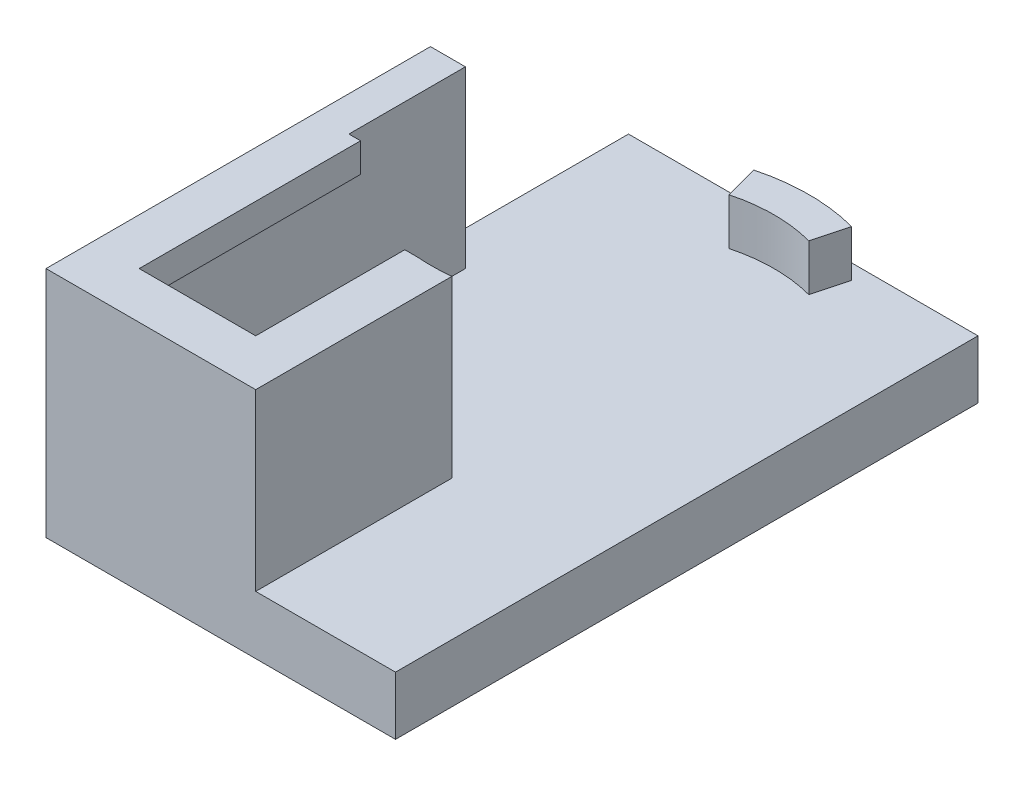
SolidWorks part; units mm, degrees
ref_plane "Front Plane" through (0, 0, 0) normal (0, 0, 1) x (1, 0, 0)
ref_plane "Top Plane" through (0, 0, 0) normal (0, 1, 0) x (1, 0, 0)
ref_plane "Right Plane" through (0, 0, 0) normal (1, 0, 0) x (0, 0, -1)
sketch "Sketch1" plane through (0, 0, 0) normal (0, 1, 0) x (1, 0, 0)
  line L1 (-22.5, 42.5) -> (22.5, 42.5)
  line L2 (-22.5, 42.5) -> (-22.5, -42.5)
  line L3 (-22.5, -42.5) -> (22.5, -42.5)
  line L4 (22.5, 42.5) -> (22.5, -42.5)
  line L5 (-22.5, 42.5) -> (22.5, -42.5) construction
  line L6 (-22.5, -42.5) -> (22.5, 42.5) construction
  point P0 (0, 0)
  dimension "D1" = 45
  dimension "D2" = 85
extrude "Boss-Extrude1" add sketch "Sketch1" along normal blind 100
shell "Shell1" thickness 5
sketch "Sketch2" plane through (0, 5, 0) normal (0, 1, 0) x (1, 0, 0)
  line L0 (-13.25, 0) -> (-13.25, -30)
  line L1 (-13.25, -30) -> (-1.25, -30)
  line L2 (-1.25, -30) -> (-1.25, -13.0576)
  line L3 (-16.25, 0) -> (-16.25, -33)
  line L4 (-16.25, -33) -> (1.75, -33)
  line L5 (1.75, -33) -> (1.75, -13.0576)
  line L6 (-13.25, 0) -> (-16.25, 0)
  line L7 (3.4294, 12.7985) -> (4.2058, 15.6963)
  line L8 (-4.2058, 15.6963) -> (-3.4294, 12.7985)
  line L19 (-1.25, -13.0576) -> (-1.25, -16.2019)
  line L20 (-13.25, -25) -> (-16.25, -25)
  line L21 (-16.25, -15) -> (-13.25, -15)
  circle A1 centre (0, 0) radius 16.25
  circle A2 centre (0, 0) radius 13.25
  dimension "D1" = 26.5
  dimension "D2" = 32.5
  dimension "D3" = 12
  dimension "D4" = 30
  dimension "D6" = 15
  dimension "D8" = 10
  dimension "D9" = 8
  dimension "D5" = 3
extrude "Boss-Extrude2" add sketch "Sketch2" along normal blind 15 contours A1 L2 L1 L0 L20 L3 L4 L5 | L21 L3 L20 L0 | A1 L3 L21 L0 | A2 L7 A1 L8 | L6 A1 L0
sketch "Sketch4" plane through (-13.25, 0, 0) normal (1, 0, 0) x (0, 0, -1)
  line L0 (0, 5) -> (-30, 5) construction
  line L1 (-30, 20) -> (-10, 20)
  line L2 (-30, 20) -> (-30, 17.5)
  line L3 (-30, 17.5) -> (-10, 17.5)
  line L4 (-10, 20) -> (-10, 17.5)
  dimension "D1" = 12.5
  dimension "D2" = 20
extrude "Boss-Extrude3" add sketch "Sketch4" along normal blind 1
sketch "Sketch5" plane through (-1.25, 0, 0) normal (-1, 0, 0) x (0, 0, 1)
  line L0 (30, 20) -> (30, 5) construction
  line L1 (16.2019, 20) -> (30, 20)
  line L2 (16.2019, 20) -> (16.2019, 17.5)
  line L3 (16.2019, 17.5) -> (30, 17.5)
  line L4 (30, 20) -> (30, 17.5)
  line L5 (30, 5) -> (16.2019, 5) construction
  dimension "D1" = 12.5
extrude "Boss-Extrude4" add sketch "Sketch5" along normal blind 1
sketch "Sketch6" plane through (0, 0, 30) normal (0, 0, -1) x (-1, 0, 0)
  line L2 (12.25, 17.5) -> (2.25, 17.5)
  line L3 (12.25, 17.5) -> (12.25, 20)
  line L4 (12.25, 20) -> (2.25, 20)
  line L5 (2.25, 17.5) -> (2.25, 20)
extrude "Boss-Extrude5" add sketch "Sketch6" along normal blind 1
sketch "Sketch9" plane through (0, 20, 0) normal (0, 1, 0) x (1, 0, 0)
  line L1 (-5.0753, 17.3777) -> (5.4023, 17.3777)
  line L2 (-5.0753, 17.3777) -> (-5.0753, 11.055)
  line L3 (-5.0753, 11.055) -> (5.4023, 11.055)
  line L4 (5.4023, 17.3777) -> (5.4023, 11.055)
extrude "Cut-Extrude1" cut sketch "Sketch9" against normal blind 11
sketch "Sketch10" plane through (0, 5, 0) normal (0, 1, 0) x (1, 0, 0)
  line L1 (13.75, 17) -> (-16.25, 17)
  line L2 (13.75, 17) -> (13.75, -33)
  line L3 (13.75, -33) -> (-16.25, -33)
  line L4 (-16.25, 17) -> (-16.25, -33)
  line L5 (-25.747, -45.8391) -> (28.4861, -45.8391)
  line L6 (-25.747, -45.8391) -> (-25.747, 48.035)
  line L7 (-25.747, 48.035) -> (28.4861, 48.035)
  line L8 (28.4861, -45.8391) -> (28.4861, 48.035)
  dimension "D1" = 30
  dimension "D2" = 50
extrude "Cut-Extrude2" cut sketch "Sketch10" against normal through all and the other way through all
